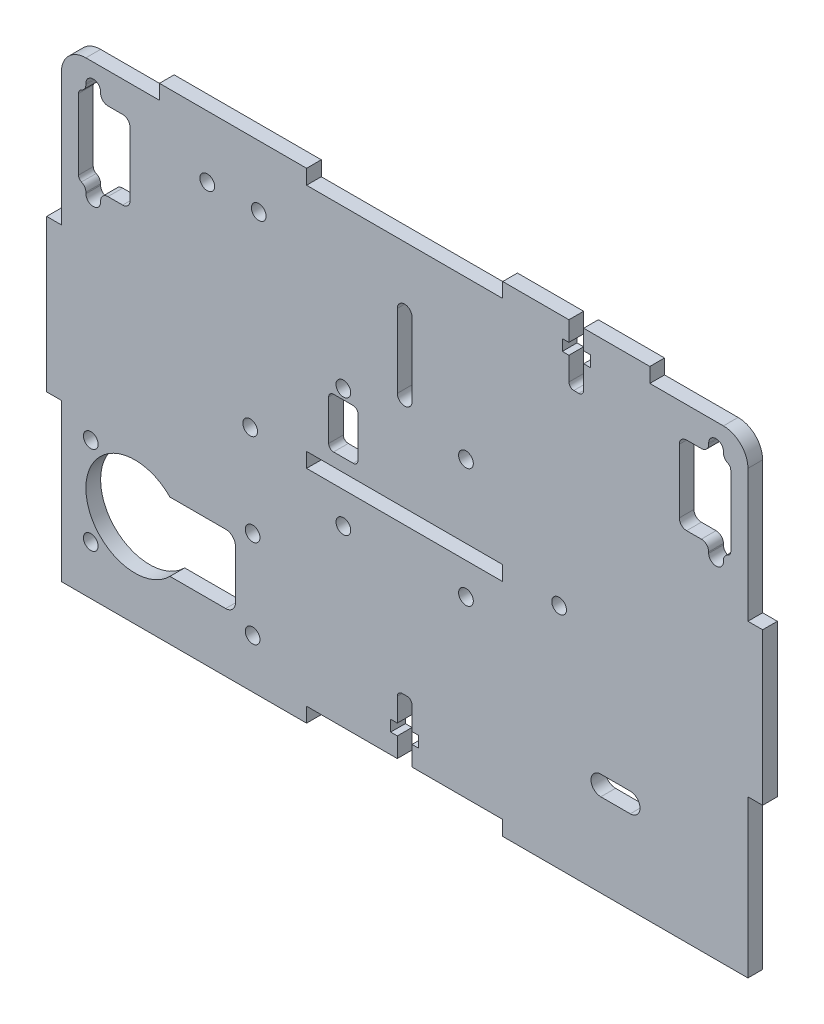
SolidWorks part; units mm, degrees
other "Marcação1"
sketch "Esboço7" plane through (-68, 31.5, 3) normal (-0.6758, 0.2828, 0.6807) x (0.7271, 0.1043, 0.6785)
sketch "Esboço8" plane through (-68, 31.5, 3) normal (-0.6758, 0.2828, 0.6807) x (0.7271, 0.1043, 0.6785)
sketch "Esboço9" plane through (-68, 31.5, 3) normal (-0.6758, 0.2828, 0.6807) x (0.7271, 0.1043, 0.6785)
sketch "Esboço10" plane through (-68, 31.5, 3) normal (-0.6758, 0.2828, 0.6807) x (0.7271, 0.1043, 0.6785)
sketch "Esboço11" plane through (-68, 36.25, 3) normal (-0.6758, 0.2828, 0.6807) x (0.7271, 0.1043, 0.6785)
sketch "Esboço13" plane through (-68, 36.25, 3) normal (-0.6758, 0.2828, 0.6807) x (0.7271, 0.1043, 0.6785)
sketch "Esboço15" plane through (-68, 36.25, 3) normal (-0.6758, 0.2828, 0.6807) x (0.7271, 0.1043, 0.6785)
sketch "Esboço19" plane through (-68, 66.25, 3) normal (-0.6758, 0.2828, 0.6807) x (0.7271, 0.1043, 0.6785)
sketch "Esboço22" plane through (-68, 95.5577, 3) normal (-0.6758, 0.2828, 0.6807) x (0.7271, 0.1043, 0.6785)
material "Acrylic (Medium-high impact)"
ref_plane "Plano frontal" through (0, 0, 0) normal (0, 0, 1) x (1, 0, 0)
ref_plane "Plano superior" through (0, 0, 0) normal (0, 1, 0) x (1, 0, 0)
ref_plane "Plano direito" through (0, 0, 0) normal (1, 0, 0) x (0, 0, -1)
sketch "Esboço1" plane through (0, 0, 0) normal (0, 0, 1) x (1, 0, 0)
  line L6 (70, -47.5) -> (-70, -47.5)
  line L8 (70, -47.5) -> (70, 47.5)
  line L9 (70, 47.5) -> (-70, 47.5)
  line L10 (-70, -47.5) -> (-70, 47.5)
  line L11 (70, -47.5) -> (-70, 47.5) construction
  line L12 (70, 47.5) -> (-70, -47.5) construction
  point P0 (0, 0)
  dimension "D1" = 95
  dimension "D2" = 140
extrude "Ressalto-extrusão1" add sketch "Esboço1" along normal mid plane 3
sketch "Esboço2" plane through (0, 0, 1.5) normal (0, 0, 1) x (1, 0, 0)
  line L1 (-20, -47.5) -> (20, -47.5)
  line L2 (-20, -47.5) -> (-20, -44.5)
  line L3 (-20, -44.5) -> (20, -44.5)
  line L4 (20, -47.5) -> (20, -44.5)
  line L6 (-70, -47.5) -> (70, -47.5) construction
  line L21 (-20, 0.5) -> (20, 0.5)
  line L22 (-20, 0.5) -> (-20, -2.5)
  line L23 (-20, -2.5) -> (20, -2.5)
  line L24 (20, 0.5) -> (20, -2.5)
  line L25 (-20, 0.5) -> (20, -2.5) construction
  line L26 (-20, -2.5) -> (20, 0.5) construction
  line L28 (0, -1.65) -> (0, 1.65) construction
  circle A2 centre (-31.5, -1) radius 1.5
  circle A4 centre (31.5, -1) radius 1.5
  point P6 (0, -44.5)
  point P14 (0, -1)
  point P29 (-20, -1)
  dimension "D4" = 11.5
  dimension "D8" = 3
  dimension "D3" = 3
  dimension "D2" = 40
  dimension "D5" = 45
  dimension "D6" = 3
  dimension "D13" = 40
extrude "Corte-extrusão1" cut sketch "Esboço2" against normal through all
sketch "Sketch9" plane through (0, 0, 0) normal (0, 0, 1) x (1, 0, 0)
  line L0 (20, -44.5) -> (-20, -44.5) construction
  line L1 (-1.5, -44.5) -> (1.5, -44.5)
  line L2 (-1.5, -44.5) -> (-1.5, -40.5)
  line L3 (-0.5, -32.5) -> (0.5, -32.5)
  line L4 (1.5, -44.5) -> (1.5, -40.5)
  line L5 (1.5, -38.23) -> (2.85, -38.23)
  line L6 (-2.85, -38.23) -> (-1.5, -38.23)
  line L7 (-2.85, -38.23) -> (-2.85, -40.5)
  line L8 (-2.85, -40.5) -> (-1.5, -40.5)
  line L9 (2.85, -38.23) -> (2.85, -40.5)
  line L10 (-1.5, -38.23) -> (-1.5, -33.5)
  line L11 (1.5, -40.5) -> (2.85, -40.5)
  line L12 (1.5, -38.23) -> (1.5, -33.5)
  arc A0 (0.5, -32.5) -> (1.5, -33.5) centre (0.5, -33.5) cw
  arc A1 (-1.5, -33.5) -> (-0.5, -32.5) centre (-0.5, -33.5) cw
  point P6 (0, -32.5)
  point P18 (1.5, -32.5)
  point P21 (-1.5, -32.5)
  dimension "D7" = 1
  dimension "D1" = 3
  dimension "D2" = 12
  dimension "D3" = 2.27
  dimension "D4" = 1.35
  dimension "D5" = 1.35
  dimension "D6" = 4
extrude "Cut-Extrude12" cut sketch "Sketch9" against normal through all both and the other way through all
sketch "Esboço3" plane through (0, 0, 1.5) normal (0, 0, 1) x (1, 0, 0)
  line L0 (70, -47.5) -> (70, 47.5) construction
  line L1 (70, 15.5) -> (73, 15.5)
  line L2 (70, 15.5) -> (70, -15.5)
  line L3 (70, -15.5) -> (73, -15.5)
  line L4 (73, 15.5) -> (73, -15.5)
  line L5 (0, -1.65) -> (0, 1.65) construction
  line L6 (-70, -15.5) -> (-73, -15.5)
  line L7 (-70, 15.5) -> (-73, 15.5)
  line L8 (-70, 15.5) -> (-70, -15.5)
  line L9 (-73, 15.5) -> (-73, -15.5)
  line L15 (70, 47.5) -> (-70, 47.5) construction
  line L16 (-50, 47.5) -> (-20, 47.5)
  line L17 (-50, 47.5) -> (-50, 50.5)
  line L18 (-50, 50.5) -> (-20, 50.5)
  line L19 (-20, 47.5) -> (-20, 50.5)
  line L20 (20, 47.5) -> (20, 50.5)
  line L21 (50, 50.5) -> (20, 50.5)
  line L22 (50, 47.5) -> (50, 50.5)
  line L23 (50, 47.5) -> (20, 47.5)
  line L24 (-70, 47.5) -> (-70, -47.5) construction
  point P6 (70, 0)
  dimension "D1" = 3
  dimension "D2" = 31
  dimension "D3" = 30
  dimension "D4" = 20
  dimension "D5" = 20
extrude "Ressalto-extrusão2" add sketch "Esboço3" against normal through all
sketch "Esboço30" plane through (0, 0, -1.5) normal (0, 0, -1) x (-1, 0, 0)
  line L1 (36.5, -21.5) -> (47.8586, -21.5)
  line L2 (70, 47.5) -> (70, 15.5) construction
  line L3 (70, -47.5) -> (20, -47.5) construction
  line L4 (34.5, -23.5) -> (34.5, -33.5)
  line L5 (36.5, -35.5) -> (47.8586, -35.5)
  arc A0 (47.8586, -35.5) -> (47.8586, -21.5) centre (55, -28.5) ccw
  circle A1 centre (55, -28.5) radius 10 construction
  arc A2 (34.5, -33.5) -> (36.5, -35.5) centre (36.5, -33.5) ccw
  arc A3 (36.5, -21.5) -> (34.5, -23.5) centre (36.5, -23.5) ccw
  point P6 (34.5, -28.5)
  point P12 (34.5, -35.5)
  point P16 (34.5, -21.5)
  dimension "D1" = 20
  dimension "D2" = 15
  dimension "D3" = 19
  dimension "D6" = 2
  dimension "D4" = 10.5
  dimension "D5" = 14
extrude "Corte-extrusão11" cut sketch "Esboço30" against normal through all both and the other way through all
sketch "Esboço4" plane through (0, 0, 1.5) normal (0, 0, 1) x (1, 0, 0)
  line L0 (40, -28.5) -> (46, -28.5) construction
  line L1 (40, -26.5) -> (46, -26.5)
  line L2 (40, -30.5) -> (46, -30.5)
  arc A9 (40, -26.5) -> (40, -30.5) centre (40, -28.5) ccw
  circle A10 centre (43, -28.5) radius 2 construction
  arc A11 (-47.8586, -21.5) -> (-47.8586, -35.5) centre (-55, -28.5) ccw construction
  arc A12 (46, -30.5) -> (46, -26.5) centre (46, -28.5) ccw
  point P5 (-65, -28.5)
  point P8 (43, -28.5)
  dimension "D1" = 98
  dimension "D3" = 3
  dimension "D2" = 4
extrude "Corte-extrusão2" cut sketch "Esboço4" against normal through all
sketch "Esboço31" plane through (0, 0, -1.5) normal (0, 0, -1) x (-1, 0, 0)
  circle A4 centre (64, -19.5) radius 1.5
  circle A5 centre (64, -37.5) radius 1.5
  circle A6 centre (55, -28.5) radius 10 construction
  circle A7 centre (31, -19.5) radius 1.5
  circle A8 centre (31, -37.5) radius 1.5
  dimension "D1" = 3
  dimension "D2" = 9
  dimension "D3" = 9
  dimension "D4" = 18
  dimension "D5" = 33
extrude "Corte-extrusão12" cut sketch "Esboço31" against normal through all both and the other way through all
sketch "Sketch8" plane through (0, 0, -1.5) normal (0, 0, -1) x (-1, 0, 0)
  line L2 (-70, 47.5) -> (-50, 47.5) construction
  line L4 (0, 1.65) -> (0, -1.65) construction
  line L5 (-70, 15.5) -> (-70, 47.5) construction
  line B0 (-70, 33.25) -> (-56, 33.25) construction
  line B1 (-70, 39.75) -> (-70, 26.75) construction
  line B2 (-56, 39.75) -> (-56, 26.75)
  line B3 (-65, 23.5) -> (-65, 23.75)
  line B4 (-62, 23.5) -> (-62, 23.75)
  line B5 (-60.5, 25.25) -> (-57.5, 25.25)
  line B6 (-65, 43) -> (-65, 42.75)
  line B7 (-62, 43) -> (-62, 42.75)
  line B8 (-60.5, 41.25) -> (-57.5, 41.25)
  line B9 (-66.5, 40.4587) -> (-66.5, 26.0413)
  arc B10 (-62, 43) -> (-65, 43) centre (-63.5, 43) ccw
  arc B11 (-65, 23.5) -> (-62, 23.5) centre (-63.5, 23.5) ccw
  arc B12 (-62, 23.75) -> (-60.5, 25.25) centre (-60.5, 23.75) cw
  arc B13 (-65, 23.75) -> (-65.9, 25.1248) centre (-66.5, 23.75) ccw
  arc B14 (-62, 42.75) -> (-60.5, 41.25) centre (-60.5, 42.75) ccw
  arc B15 (-65, 42.75) -> (-65.9, 41.3752) centre (-66.5, 42.75) cw
  arc B16 (-57.5, 25.25) -> (-56, 26.75) centre (-57.5, 26.75) ccw
  arc B17 (-57.5, 41.25) -> (-56, 39.75) centre (-57.5, 39.75) cw
  arc B18 (-66.5, 26.0413) -> (-65.9, 25.1248) centre (-65.5, 26.0413) ccw
  arc B19 (-66.5, 40.4587) -> (-65.9, 41.3752) centre (-65.5, 40.4587) cw
  line B20 (70, 33.25) -> (56, 33.25) construction
  line B21 (56, 39.75) -> (56, 26.75)
  line B22 (65, 23.5) -> (65, 23.75)
  line B23 (62, 23.5) -> (62, 23.75)
  line B24 (60.5, 25.25) -> (57.5, 25.25)
  line B25 (65, 43) -> (65, 42.75)
  line B26 (62, 43) -> (62, 42.75)
  line B27 (60.5, 41.25) -> (57.5, 41.25)
  line B28 (66.5, 40.4587) -> (66.5, 26.0413)
  arc B29 (62, 43) -> (65, 43) centre (63.5, 43) cw
  arc B30 (65, 23.5) -> (62, 23.5) centre (63.5, 23.5) cw
  arc B31 (62, 23.75) -> (60.5, 25.25) centre (60.5, 23.75) ccw
  arc B32 (65, 23.75) -> (65.9, 25.1248) centre (66.5, 23.75) cw
  arc B33 (62, 42.75) -> (60.5, 41.25) centre (60.5, 42.75) cw
  arc B34 (65, 42.75) -> (65.9, 41.3752) centre (66.5, 42.75) ccw
  arc B35 (57.5, 25.25) -> (56, 26.75) centre (57.5, 26.75) cw
  arc B36 (57.5, 41.25) -> (56, 39.75) centre (57.5, 39.75) ccw
  arc B37 (66.5, 26.0413) -> (65.9, 25.1248) centre (65.5, 26.0413) cw
  arc B38 (66.5, 40.4587) -> (65.9, 41.3752) centre (65.5, 40.4587) ccw
  dimension "D3" = 3
sketch_block_instance "Block6-1"
sketch_block "Block6" parameters "D1"=3, "D2"=1.5, "D3"=1.5, "D5"=1, "D4"=5, "D6"=6.5
sketch_block_instance "Block6-4"
extrude "Cut-Extrude11" cut sketch "Sketch8" against normal through all both and the other way through all
sketch "Sketch11" plane through (0, 0, 0) normal (0, 0, 1) x (1, 0, 0)
  line L0 (50, 50.5) -> (20, 50.5) construction
  line L1 (33.5, 50.5) -> (36.5, 50.5)
  line L2 (33.5, 50.5) -> (33.5, 46.5)
  line L3 (34.5, 38.5) -> (35.5, 38.5)
  line L4 (36.5, 50.5) -> (36.5, 46.5)
  line L5 (20, 50.5) -> (20, 47.5) construction
  line L6 (33.5, 44.23) -> (33.5, 39.5)
  line L7 (32.15, 46.5) -> (33.5, 46.5)
  line L8 (32.15, 46.5) -> (32.15, 44.23)
  line L9 (32.15, 44.23) -> (33.5, 44.23)
  line L10 (37.85, 46.5) -> (37.85, 44.23)
  line L11 (36.5, 46.5) -> (37.85, 46.5)
  line L12 (36.5, 44.23) -> (36.5, 39.5)
  line L13 (36.5, 44.23) -> (37.85, 44.23)
  arc A0 (35.5, 38.5) -> (36.5, 39.5) centre (35.5, 39.5) ccw
  arc A1 (33.5, 39.5) -> (34.5, 38.5) centre (34.5, 39.5) ccw
  point P20 (33.5, 38.5)
  dimension "D8" = 1
  dimension "D1" = 3
  dimension "D2" = 12
  dimension "D3" = 13.5
  dimension "D4" = 1.35
  dimension "D5" = 2.27
  dimension "D6" = 1.35
  dimension "D7" = 4
extrude "Cut-Extrude14" cut sketch "Sketch11" against normal through all both and the other way through all
sketch "Sketch12" plane through (0, 0, 1.5) normal (0, 0, 1) x (1, 0, 0)
  line L0 (0, 0.5) -> (0, 47.5) construction
  line L1 (20, 0.5) -> (-20, 0.5) construction
  line L2 (20, 47.5) -> (-20, 47.5) construction
  line L3 (0, 20) -> (0, 35) construction
  line L6 (-1.5, 20) -> (-1.5, 35)
  line L7 (1.5, 20) -> (1.5, 35)
  circle A1 centre (0, 20) radius 1.5 construction
  arc A4 (-1.5, 20) -> (1.5, 20) centre (0, 20) ccw
  arc A5 (1.5, 35) -> (-1.5, 35) centre (0, 35) ccw
  point P4 (0, 27.5)
  dimension "D1" = 3
  dimension "D2" = 15
  dimension "D4" = 18
extrude "Cut-Extrude15" cut sketch "Sketch12" against normal through all
sketch "Sketch13" plane through (0, 0, 0) normal (0, 0, 1) x (1, 0, 0)
  line L15 (20, 0.5) -> (-20, 0.5) construction
  line L16 (20, -2.5) -> (20, 0.5) construction
  line L18 (-10.5, 13.35) -> (-14.5, 13.35)
  line L19 (-9.5, 12.35) -> (-9.5, 4.15)
  line L20 (-10.5, 3.15) -> (-14.5, 3.15)
  line L21 (-15.5, 12.35) -> (-15.5, 4.15)
  circle A1 centre (12.5, 15.35) radius 1.5
  circle A2 centre (-12.5, -8.95) radius 1.5
  circle A3 centre (12.5, -8.95) radius 1.5
  circle A10 centre (-12.5, 15.35) radius 1.5
  arc A11 (-14.5, 3.15) -> (-15.5, 4.15) centre (-14.5, 4.15) cw
  arc A12 (-9.5, 4.15) -> (-10.5, 3.15) centre (-10.5, 4.15) cw
  arc A13 (-14.5, 13.35) -> (-15.5, 12.35) centre (-14.5, 12.35) ccw
  arc A14 (-10.5, 13.35) -> (-9.5, 12.35) centre (-10.5, 12.35) cw
  point P16 (-12.5, 13.35)
  point P19 (-15.5, 3.15)
  point P25 (-15.5, 13.35)
  dimension "D5" = 7.5
  dimension "D1" = 3
  dimension "D3" = 25
  dimension "D2" = 24.3
  dimension "D6" = 0.5
  dimension "D4" = 13.35
  dimension "D9" = 1
  dimension "D7" = 10.2
  dimension "D8" = 1.5
extrude "Cut-Extrude16" cut sketch "Sketch13" against normal through all both and the other way through all
fillet "Fillet1" radius 5 2 edges at (70, 47.5, 0) (-70, 47.5, 0)
sketch "Sketch14" plane through (0, 0, 0) normal (0, 0, 1) x (1, 0, 0)
  line L0 (-35, 42.1706) -> (-35, 58.8294) construction
  line L2 (-20, 50.5) -> (-50, 50.5) construction
  line L3 (20, 47.5) -> (-20, 47.5) construction
  circle A0 centre (-29.75, 37.9) radius 1.5
  circle A1 centre (-40.25, 37.9) radius 1.5
  point P3 (0, 0)
  point P5 (-35, 50.5)
  dimension "D1" = 3
  dimension "D2" = 10.5
  dimension "D3" = 9.6
extrude "Cut-Extrude17" cut sketch "Sketch14" against normal through all both and the other way through all
